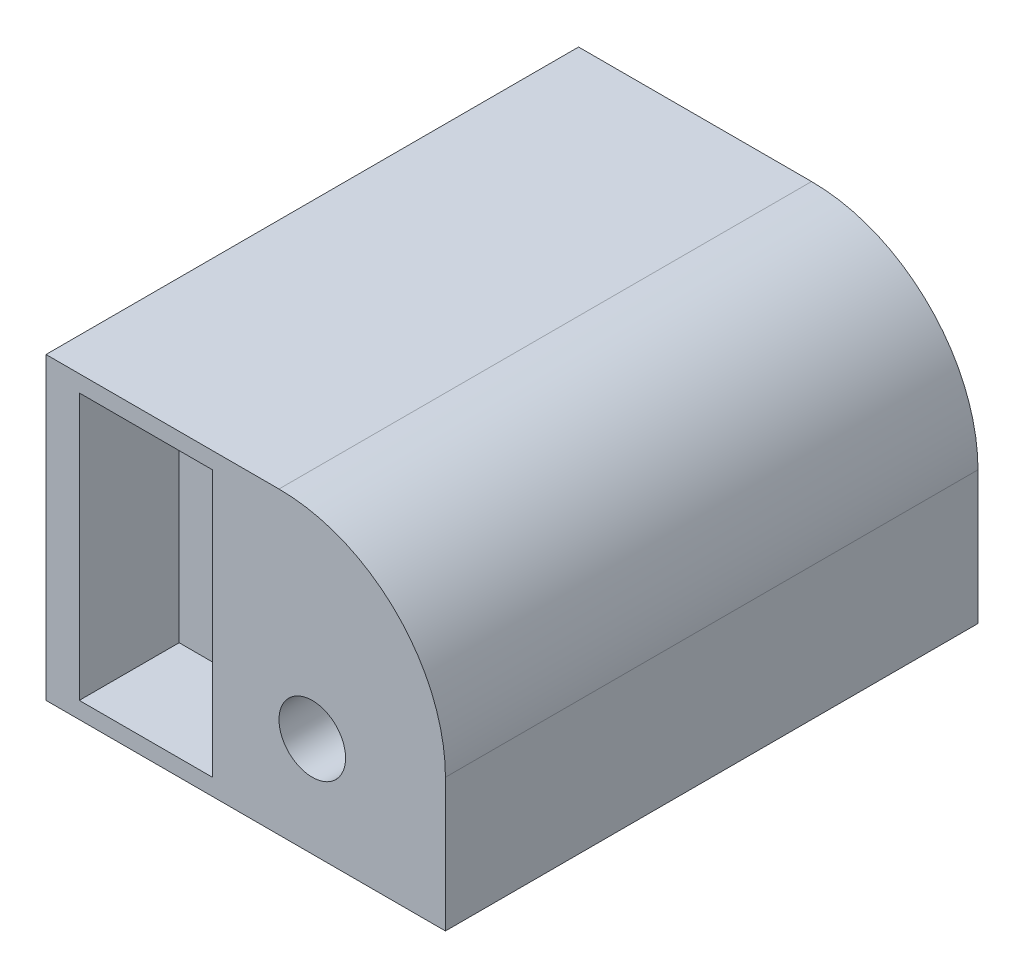
SolidWorks part; units mm, degrees
ref_plane "Front Plane" through (0, 0, 0) normal (0, 0, 1) x (1, 0, 0)
ref_plane "Top Plane" through (0, 0, 0) normal (0, 1, 0) x (1, 0, 0)
ref_plane "Right Plane" through (0, 0, 0) normal (1, 0, 0) x (0, 0, -1)
sketch "Sketch1" plane through (0, 0, 0) normal (0, 0, 1) x (1, 0, 0)
  line L1 (-43.031, 38.4488) -> (33.169, 38.4488)
  line L2 (-43.031, 38.4488) -> (-43.031, -18.7012)
  line L3 (-43.031, -18.7012) -> (33.169, -18.7012)
  line L4 (33.169, 38.4488) -> (33.169, -18.7012)
  circle A0 centre (7.769, 0.3488) radius 6.35
  dimension "D3" = 25.4
  dimension "D4" = 19.05
  dimension "D1" = 76.2
  dimension "D2" = 57.15
extrude "Boss-Extrude1" add sketch "Sketch1" along normal blind 101.6
sketch "Sketch2" plane through (-43.031, 0, 0) normal (-1, 0, 0) x (0, 0, 1)
  line L0 (0, 38.4488) -> (0, -18.7012) construction
  line L1 (6.35, 22.5738) -> (57.15, 22.5738)
  line L2 (6.35, 22.5738) -> (6.35, -2.8262)
  line L3 (6.35, -2.8262) -> (57.15, -2.8262)
  line L4 (57.15, 22.5738) -> (57.15, -2.8262)
  line L5 (101.6, -18.7012) -> (0, -18.7012) construction
  dimension "D1" = 50.8
  dimension "D2" = 6.35
  dimension "D3" = 25.4
  dimension "D4" = 15.875
extrude "Cut-Extrude1" cut sketch "Sketch2" against normal blind 19.05
sketch "Sketch3" plane through (0, 0, 101.6) normal (0, 0, 1) x (1, 0, 0)
  line L0 (-43.031, -18.7012) -> (33.169, -18.7012) construction
  line L1 (-36.681, 35.2738) -> (-11.281, 35.2738)
  line L2 (-36.681, 35.2738) -> (-36.681, -15.5262)
  line L3 (-36.681, -15.5262) -> (-11.281, -15.5262)
  line L4 (-11.281, 35.2738) -> (-11.281, -15.5262)
  line L5 (-43.031, 38.4488) -> (-43.031, -18.7012) construction
  dimension "D1" = 25.4
  dimension "D2" = 50.8
  dimension "D3" = 3.175
  dimension "D4" = 6.35
extrude "Cut-Extrude2" cut sketch "Sketch3" against normal blind 19.05
sketch "Sketch4" plane through (-23.981, 0, 0) normal (-1, 0, 0) x (0, 0, 1)
  line L0 (57.15, -2.8262) -> (57.15, 22.5738) construction
  line L1 (57.15, 22.5738) -> (6.35, 22.5738) construction
  circle A0 centre (44.45, 9.8738) radius 6.35
  dimension "D1" = 12.7
  dimension "D3" = 12.7
  dimension "D2" = 12.7
extrude "Boss-Extrude2" add sketch "Sketch4" along normal blind 2.54
fillet "Fillet1" radius 31.75 1 edges at (33.169, 38.4488, 50.8)
